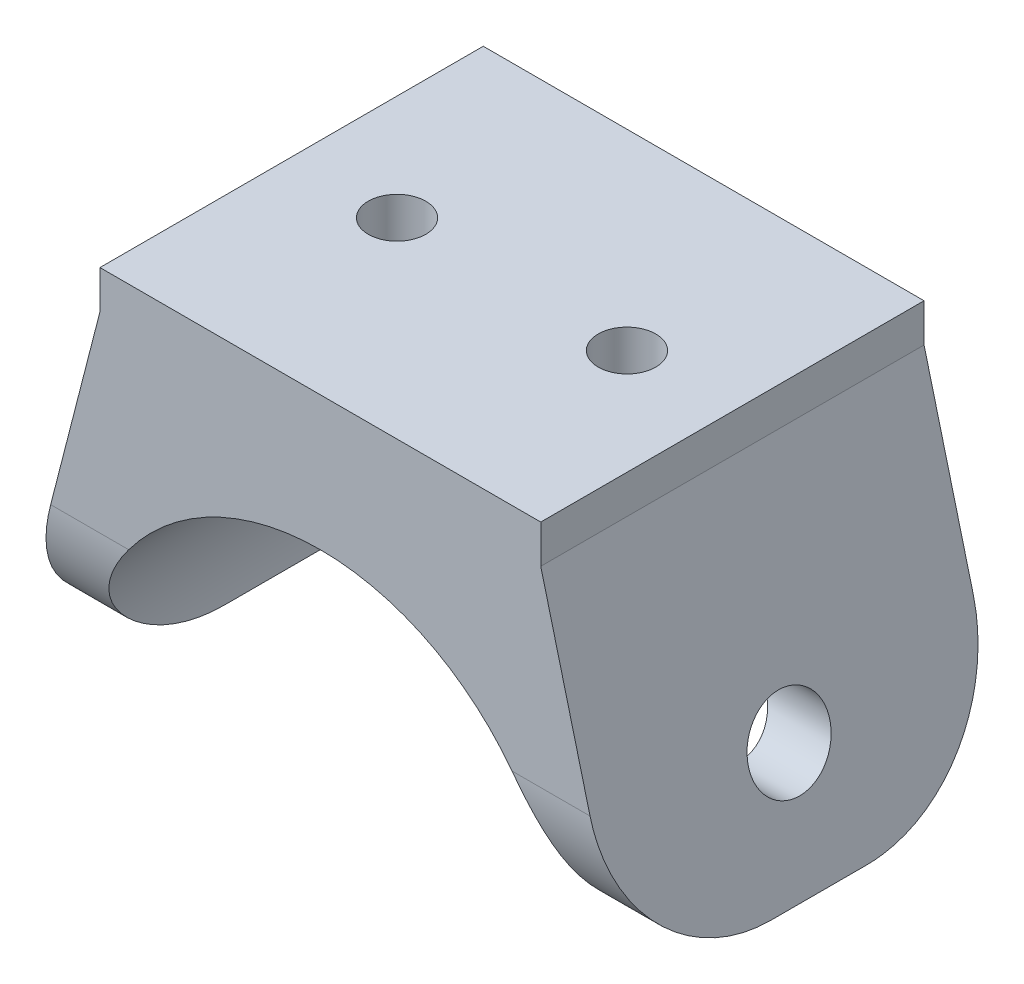
SolidWorks part; units mm, degrees
ref_plane "Front Plane" through (0, 0, 0) normal (0, 0, 1) x (1, 0, 0)
ref_plane "Top Plane" through (0, 0, 0) normal (0, 1, 0) x (1, 0, 0)
ref_plane "Right Plane" through (0, 0, 0) normal (1, 0, 0) x (0, 0, -1)
sketch "Sketch1" plane through (0, 0, 0) normal (1, 0, 0) x (0, 0, -1)
  line L1 (-5, -19.5) -> (5, -19.5)
  line L2 (-20, -4.5) -> (-20, 19.5)
  line L3 (-20, 19.5) -> (20, 19.5)
  line L4 (20, -4.5) -> (20, 19.5)
  line L5 (-20, -19.5) -> (20, 19.5) construction
  line L6 (-20, 19.5) -> (20, -19.5) construction
  circle A0 centre (0, -7.5) radius 4.25
  arc A1 (5, -19.5) -> (20, -4.5) centre (5, -4.5) ccw
  arc A2 (-5, -19.5) -> (-20, -4.5) centre (-5, -4.5) cw
  point P0 (0, 0)
  dimension "D3" = 8.5
  dimension "D5" = 15
  dimension "D1" = 40
  dimension "D2" = 39
  dimension "D4" = 27
extrude "Boss-Extrude1" add sketch "Sketch1" along normal mid plane 64
sketch "Sketch2" plane through (0, 0, 20) normal (0, 0, 1) x (1, 0, 0)
  line L0 (0, -19.5) -> (0, 19.5) construction
  line L1 (32, -19.5) -> (-32, -19.5) construction
  line L2 (32, 19.5) -> (-32, 19.5) construction
  line L3 (-23, 19.5) -> (23, 19.5)
  line L4 (23, 19.5) -> (23, 15.5)
  line L5 (23, 15.5) -> (32, -19.5)
  line L6 (32, -19.5) -> (32, 19.5)
  line L7 (32, 19.5) -> (23, 19.5)
  line L8 (-32, -19.5) -> (-32, 19.5)
  line L9 (-32, 19.5) -> (-23, 19.5)
  line L10 (-23, 15.5) -> (-32, -19.5)
  line L11 (-23, 19.5) -> (-23, 15.5)
  circle A0 centre (0, -19.5) radius 25
  dimension "D1" = 50
  dimension "D2" = 46
  dimension "D3" = 4
extrude "Cut-Extrude1" cut sketch "Sketch2" against normal blind 64
sketch "Sketch3" plane through (0, 19.5, 0) normal (0, 1, 0) x (1, 0, 0)
  line L0 (0, 0) -> (0, 10.6542) construction
  circle A0 centre (-12, 0) radius 3
  circle A1 centre (12, 0) radius 3
  dimension "D1" = 6
  dimension "D2" = 12
extrude "Cut-Extrude2" cut sketch "Sketch3" against normal blind 14
